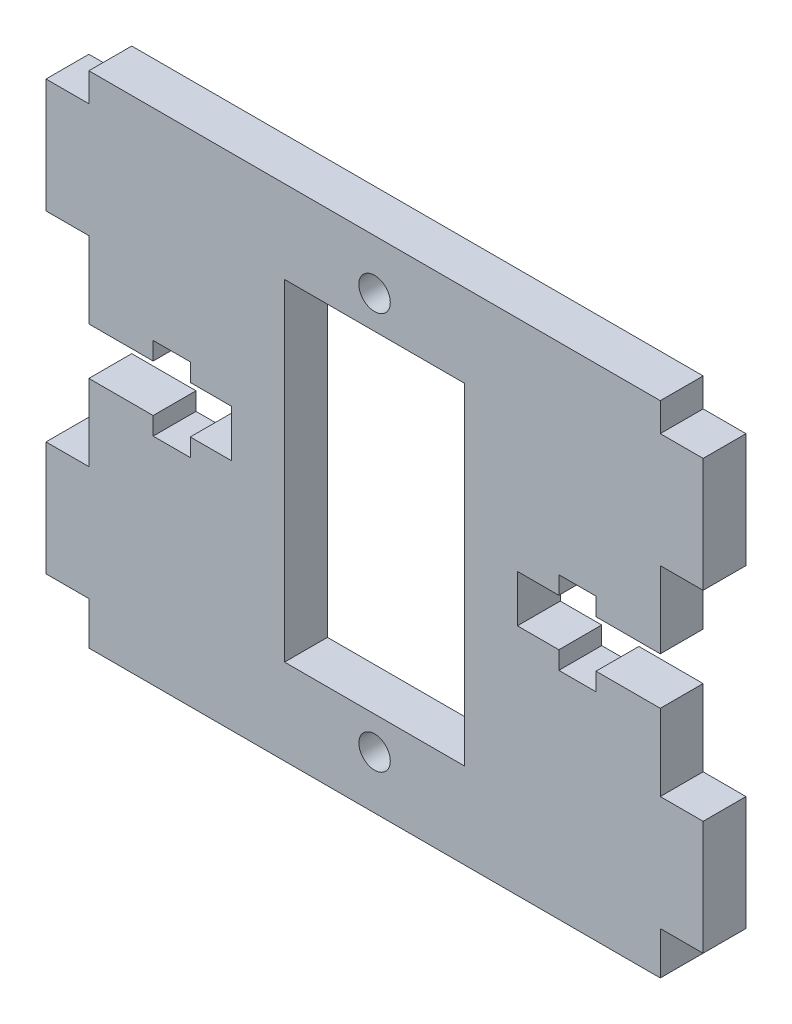
SolidWorks part; units mm, degrees
ref_plane "Спереди" through (0, 0, 0) normal (0, 0, 1) x (1, 0, 0)
ref_plane "Сверху" through (0, 0, 0) normal (0, 1, 0) x (1, 0, 0)
ref_plane "Справа" through (0, 0, 0) normal (1, 0, 0) x (0, 0, -1)
other "Configuration Table"
sketch "Eskiz_kontur" plane through (0, 0, 0) normal (0, 0, 1) x (1, 0, 0)
  line L0 (20, -3.35) -> (15.5, -3.35)
  line L1 (20, 2) -> (20, -3.35)
  line L2 (15.5, -3.35) -> (15.5, -2.1)
  line L3 (23, 2) -> (20, 2)
  line L4 (15.5, -2.1) -> (12.9, -2.1)
  line L5 (23, 10) -> (23, 2)
  line L6 (12.9, -2.1) -> (12.9, -3.35)
  line L7 (20, 10) -> (23, 10)
  line L8 (12.9, -3.35) -> (10, -3.35)
  line L9 (20, 12) -> (20, 10)
  line L10 (10, -3.35) -> (10, -6.65)
  line L11 (-20, 12) -> (20, 12)
  line L12 (10, -6.65) -> (12.9, -6.65)
  line L13 (-20, 10) -> (-20, 12)
  line L14 (12.9, -6.65) -> (12.9, -7.9)
  line L15 (-23, 10) -> (-20, 10)
  line L16 (12.9, -7.9) -> (15.5, -7.9)
  line L17 (-23, 2) -> (-23, 10)
  line L18 (15.5, -7.9) -> (15.5, -6.65)
  line L19 (-20, 2) -> (-23, 2)
  line L20 (15.5, -6.65) -> (20, -6.65)
  line L21 (-20, -3.35) -> (-20, 2)
  line L22 (20, -6.65) -> (20, -12)
  line L23 (-15.5, -3.35) -> (-20, -3.35)
  line L24 (20, -12) -> (23, -12)
  line L25 (-15.5, -2.1) -> (-15.5, -3.35)
  line L26 (23, -12) -> (23, -20)
  line L27 (-12.9, -2.1) -> (-15.5, -2.1)
  line L28 (23, -20) -> (20, -20)
  line L29 (-12.9, -3.35) -> (-12.9, -2.1)
  line L30 (20, -20) -> (20, -23)
  line L31 (-10, -3.35) -> (-12.9, -3.35)
  line L32 (20, -23) -> (-20, -23)
  line L33 (-10, -6.65) -> (-10, -3.35)
  line L34 (-20, -23) -> (-20, -20)
  line L35 (-12.9, -6.65) -> (-10, -6.65)
  line L36 (-20, -20) -> (-23, -20)
  line L37 (-12.9, -7.9) -> (-12.9, -6.65)
  line L38 (-23, -20) -> (-23, -12)
  line L39 (-15.5, -7.9) -> (-12.9, -7.9)
  line L40 (-23, -12) -> (-20, -12)
  line L41 (-15.5, -6.65) -> (-15.5, -7.9)
  line L42 (-20, -12) -> (-20, -6.65)
  line L43 (-20, -6.65) -> (-15.5, -6.65)
  line L44 (6.3, 6.2) -> (-6.3, 6.2)
  line L45 (-6.3, 6.2) -> (-6.3, -17)
  line L46 (6.3, -17) -> (6.3, 6.2)
  line L47 (-6.3, -17) -> (6.3, -17)
extrude "Plastina" add sketch "Eskiz_kontur" along normal blind 3
sketch "Eskiz_otverstiya" plane through (0, 0, 0) normal (0, 0, 1) x (1, 0, 0)
  circle A0 centre (0, -19.3) radius 1.1
  circle A1 centre (0, 8.5) radius 1.1
  dimension "d1" = 2.2
  dimension "d2" = 2.2
extrude "Otverstiya" cut sketch "Eskiz_otverstiya" against normal through all and the other way through all
equation "\"T3\" = 3"
equation "\"T5\" = 5"
equation "\"D_M3\" = 3.3"
equation "\"D_M2\" = 2.2"
equation "\"D_M3_TAP\" = 2.5"
equation "\"D_M4\" = 4.5"
equation "\"L1\" = 100"
equation "\"L2\" = 100"
equation "\"D1@Plastina\" = \"T3\""
equation "\"d1@Eskiz_otverstiya\" = \"D_M2\""
equation "\"d2@Eskiz_otverstiya\" = \"D_M2\""
